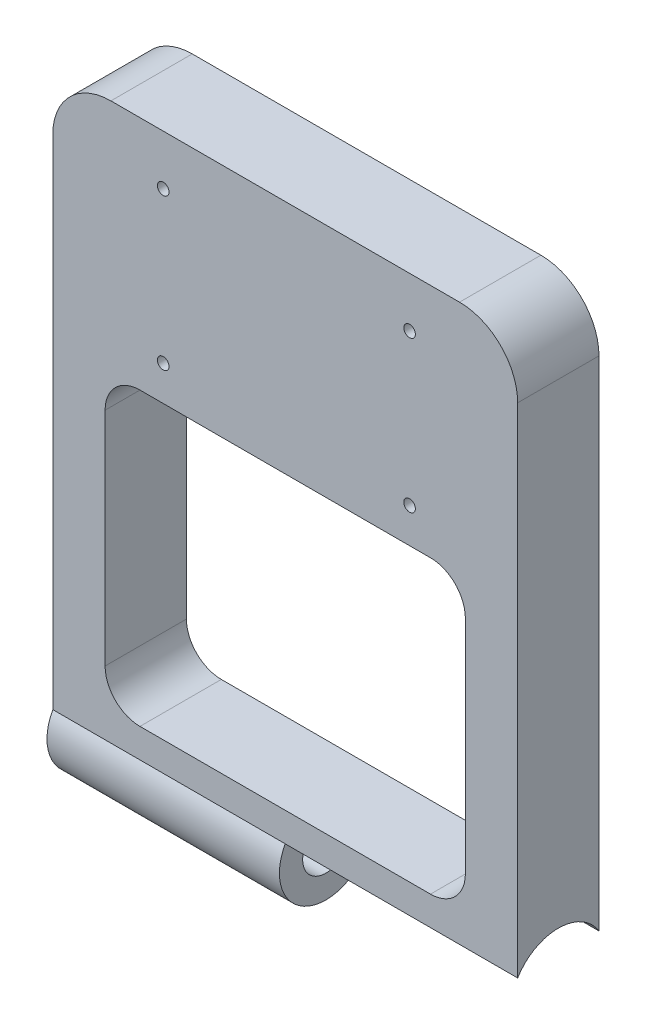
SolidWorks part; units mm, degrees
material "PLA"
ref_plane "Front Plane" through (0, 0, 0) normal (0, 0, 1) x (1, 0, 0)
ref_plane "Top Plane" through (0, 0, 0) normal (0, 1, 0) x (1, 0, 0)
ref_plane "Right Plane" through (0, 0, 0) normal (1, 0, 0) x (0, 0, -1)
sketch "Sketch1" plane through (0, 0, 0) normal (0, 0, 1) x (1, 0, 0)
  line L1 (-22.2292, 16.4644) -> (17.7708, 16.4644)
  line L2 (-22.2292, 16.4644) -> (-22.2292, -33.5356)
  line L3 (-22.2292, -33.5356) -> (17.7708, -33.5356)
  line L4 (17.7708, 16.4644) -> (17.7708, -33.5356)
  dimension "D1" = 40
  dimension "D2" = 50
extrude "Boss-Extrude1" add sketch "Sketch1" along normal blind 7
sketch "Sketch2" plane through (17.7708, 0, 0) normal (1, 0, 0) x (0, 0, -1)
  line L0 (-7, -33.5356) -> (0, -33.5356) construction
  circle A0 centre (-3.5, -33.5356) radius 4.1
  dimension "D1" = 8.2
extrude "Cut-Extrude1" cut sketch "Sketch2" against normal blind 20
ref_plane "Plane1" through (-13.2292, 0, 0) normal (1, 0, 0) x (0, 0, -1)
sketch "Sketch3" plane through (-13.2292, 0, 0) normal (1, 0, 0) x (0, 0, -1)
  circle A0 centre (-3.5, -33.3367) radius 4
  circle A1 centre (-3.5, -33.3367) radius 2
  dimension "D1" = 8
  dimension "D2" = 4
extrude "Boss-Extrude2" add sketch "Sketch3" against normal blind 9 and the other way blind 11
fillet "Fillet1" radius 5 2 edges at (-22.2292, 16.4644, 3.5) (17.7708, 16.4644, 3.5)
sketch "Sketch4" plane through (0, 0, 0) normal (0, 0, -1) x (-1, 0, 0)
  line L0 (22.2292, 11.4644) -> (22.2292, -31.4002) construction
  line L1 (17.7292, -3.8356) -> (-13.2708, -3.8356)
  line L2 (17.7292, -3.8356) -> (17.7292, -28.9002)
  line L3 (17.7292, -28.9002) -> (-13.2708, -28.9002)
  line L4 (-13.2708, -3.8356) -> (-13.2708, -28.9002)
  line L5 (22.2292, 11.4644) -> (22.2292, -31.4002) construction
  line L6 (22.2292, -31.4002) -> (2.2292, -31.4002) construction
  line L8 (-12.7708, 16.4644) -> (17.2292, 16.4644) construction
  circle A0 centre (-8.4708, 12.1644) radius 0.5
  circle A1 centre (12.7292, 12.1644) radius 0.5
  circle A2 centre (12.7292, -0.8356) radius 0.5
  circle A3 centre (-8.4708, -0.8356) radius 0.5
  dimension "D1" = 1
  dimension "D2" = 1
  dimension "D3" = 1
  dimension "D4" = 1
  dimension "D9" = 9.5
  dimension "D10" = 21.2
  dimension "D11" = 13
  dimension "D12" = 13
  dimension "D13" = 21.2
  dimension "D14" = 9.5
  dimension "D15" = 4.3
  dimension "D16" = 4.3
  dimension "D8" = 3
  dimension "D5" = 31
  dimension "D6" = 4.5
  dimension "D7" = 2.5
extrude "Cut-Extrude2" cut sketch "Sketch4" against normal through all
fillet "Fillet2" radius 3 4 edges at (13.2708, -3.8356, 3.5) (13.2708, -28.9002, 3.5) (-17.7292, -28.9002, 3.5) (-17.7292, -3.8356, 3.5)
sketch "Sketch5" plane through (-22.2292, 0, 0) normal (-1, 0, 0) x (0, 0, 1)
  circle A0 centre (3.5, -33.3367) radius 2
  arc A1 (1.5099, -33.5356) -> (5.4901, -33.5356) centre (3.5, -33.3367) ccw construction
extrude "Cut-Extrude3" cut sketch "Sketch5" against normal through all
